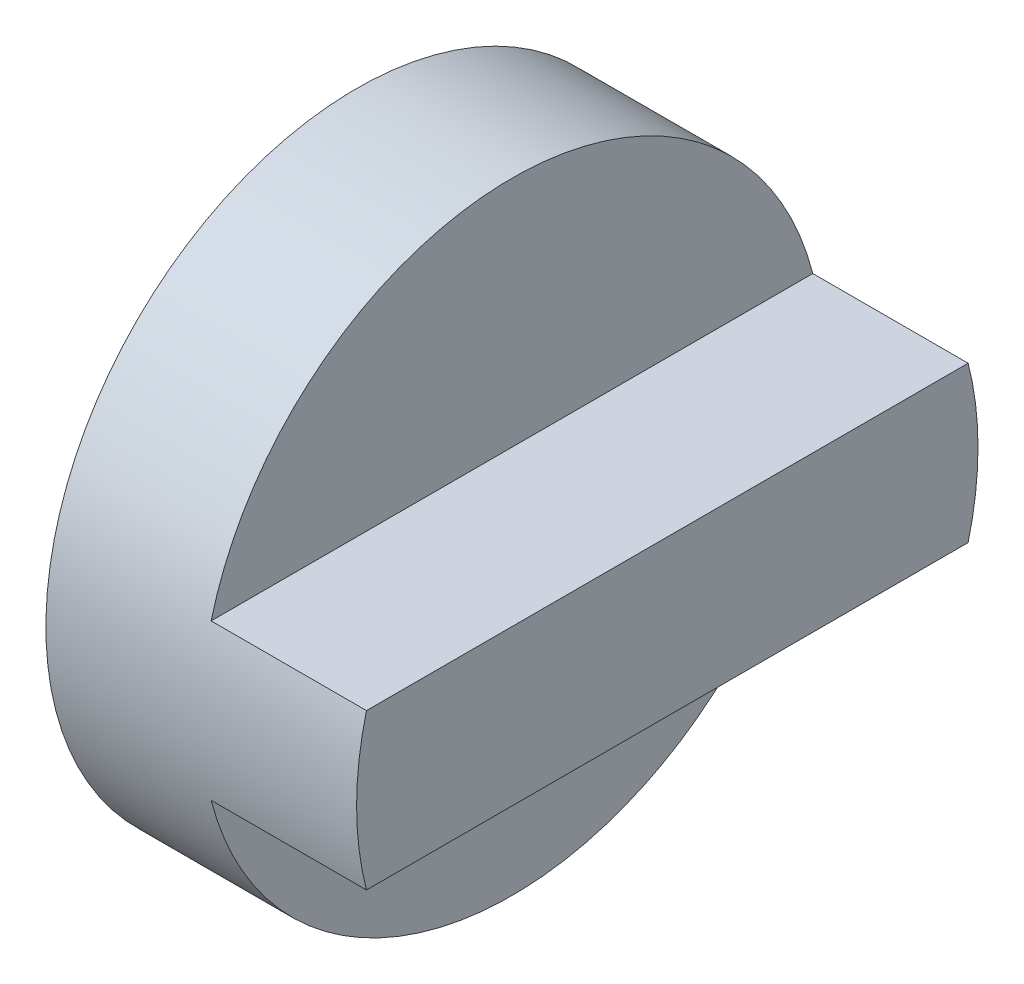
SolidWorks part; units mm, degrees
ref_plane "Front Plane" through (0, 0, 0) normal (0, 0, 1) x (1, 0, 0)
ref_plane "Top Plane" through (0, 0, 0) normal (0, 1, 0) x (1, 0, 0)
ref_plane "Right Plane" through (0, 0, 0) normal (1, 0, 0) x (0, 0, -1)
sketch "Sketch2" plane through (0, 0, 0) normal (1, 0, 0) x (0, 0, -1)
  circle A0 centre (0, 0) radius 20
  dimension "D1" = 40
extrude "Boss-Extrude1" add sketch "Sketch2" along normal blind 10
sketch "Sketch3" plane through (10, 0, 0) normal (1, 0, 0) x (0, 0, -1)
  line L0 (19.3649, 5) -> (-19.3649, 5)
  line L1 (-19.3649, -5) -> (19.3649, -5)
  circle A0 centre (0, 0) radius 20 construction
  arc A1 (-19.3649, 5) -> (-19.3649, -5) centre (0, 0) ccw
  arc A2 (19.3649, -5) -> (19.3649, 5) centre (0, 0) ccw
  point P6 (0, 0)
  dimension "D1" = 5
  dimension "D2" = 5
extrude "Boss-Extrude2" add sketch "Sketch3" along normal blind 10
